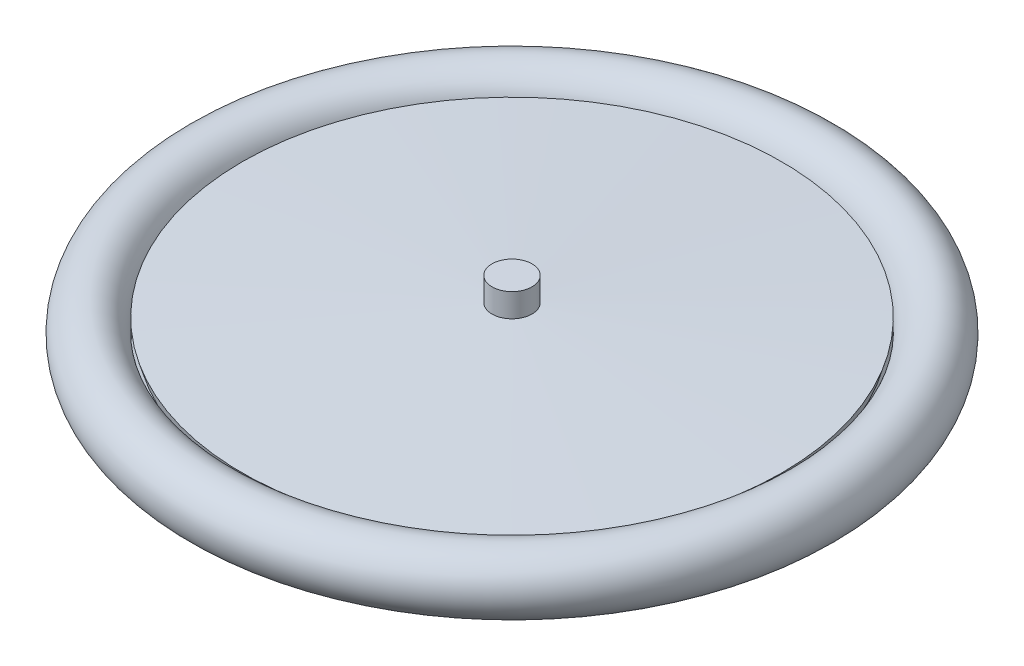
SolidWorks part; units mm, degrees
ref_plane "Plan de face" through (0, 0, 0) normal (0, 0, 1) x (1, 0, 0)
ref_plane "Plan de dessus" through (0, 0, 0) normal (0, 1, 0) x (1, 0, 0)
ref_plane "Plan de droite" through (0, 0, 0) normal (1, 0, 0) x (0, 0, -1)
sketch "Esquisse1" plane through (0, 0, 0) normal (0, 0, 1) x (1, 0, 0)
  line L0 (0, 0) -> (0, 50) construction
  line L1 (150, 25) -> (0, 25) construction
  line L2 (0, 50) -> (10, 50)
  line L3 (10, 50) -> (10, 38.1925)
  line L4 (10, 38.1925) -> (135, 31.7927)
  line L5 (135, 31.7927) -> (133.015, 25)
  line L6 (135, 18.2073) -> (133.015, 25)
  line L7 (10, 11.8075) -> (135, 18.2073)
  line L8 (10, 0) -> (10, 11.8075)
  line L9 (0, 0) -> (10, 0)
  line L10 (0, 0) -> (0, 50)
  circle A0 centre (150, 25) radius 15
  point P14 (0, 0)
  point P15 (135, 22.9016)
  point P16 (133.015, 15)
  point P17 (10, 18.2073)
  point P18 (135, 31.7927)
  point P19 (10, 38.1925)
  dimension "D1" = 30
  dimension "D2" = 150
  dimension "D3" = 50
  dimension "D4" = 20
revolve "Révolution1" add sketch "Esquisse1" angle 360 about L0
